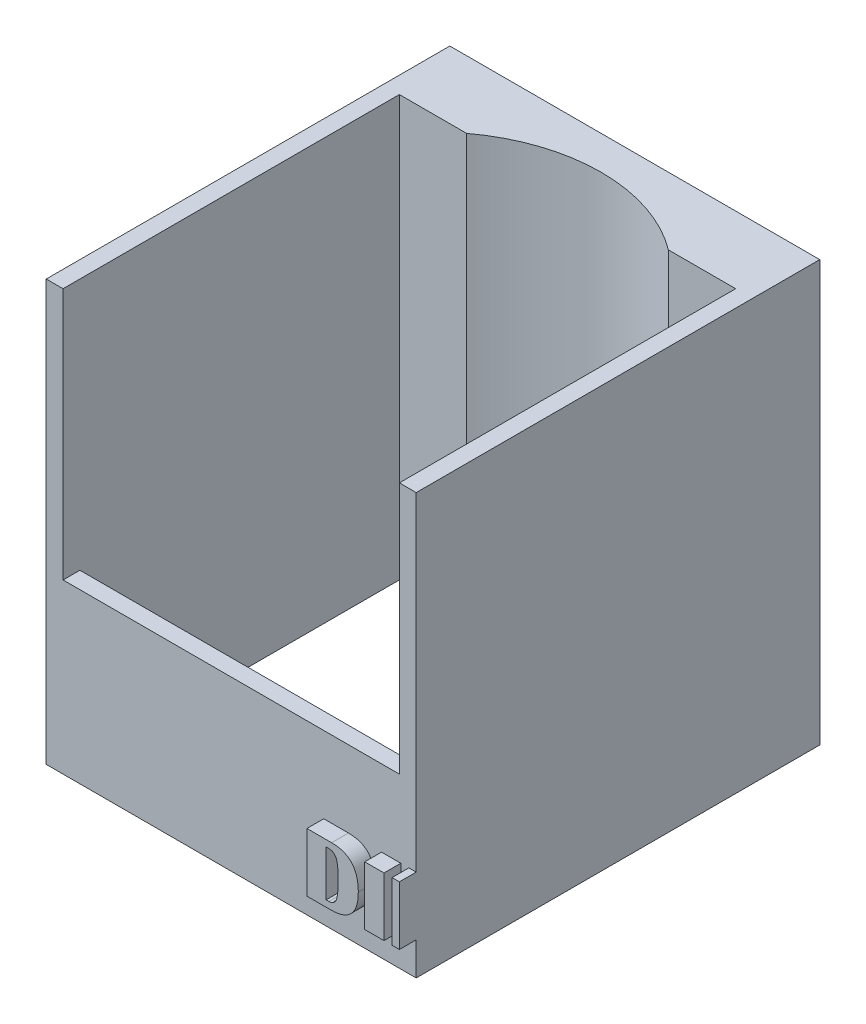
SolidWorks part; units mm, degrees
ref_plane "정면" through (0, 0, 0) normal (0, 0, 1) x (1, 0, 0)
ref_plane "윗면" through (0, 0, 0) normal (0, 1, 0) x (1, 0, 0)
ref_plane "우측면" through (0, 0, 0) normal (1, 0, 0) x (0, 0, -1)
sketch "Sketch1" plane through (0, 0, 0) normal (0, 1, 0) x (1, 0, 0)
  line L1 (0, 0) -> (670, 0)
  line L2 (0, 0) -> (0, 120)
  line L3 (0, 120) -> (670, 120)
  line L4 (670, 0) -> (670, 120)
  dimension "700" = 670
  dimension "D2" = 120
extrude "Boss-Extrude1" add sketch "Sketch1" along normal blind 530
sketch "Sketch2" plane through (0, 0, 0) normal (0, 0, 1) x (1, 0, 0)
  line L0 (0, 530) -> (0, 0) construction
  line L1 (10, 280) -> (110, 280)
  line L2 (10, 280) -> (10, 480)
  line L3 (10, 480) -> (110, 480)
  line L4 (110, 280) -> (110, 480)
  line L5 (0, 0) -> (670, 0) construction
  line L6 (120, 280) -> (120, 480)
  line L7 (120, 280) -> (220, 280)
  line L8 (220, 280) -> (220, 480)
  line L9 (120, 480) -> (220, 480)
  line L10 (230, 280) -> (230, 480)
  line L11 (230, 280) -> (330, 280)
  line L12 (330, 280) -> (330, 480)
  line L13 (230, 480) -> (330, 480)
  line L14 (340, 280) -> (340, 480)
  line L15 (340, 280) -> (440, 280)
  line L16 (440, 280) -> (440, 480)
  line L17 (340, 480) -> (440, 480)
  line L18 (450, 280) -> (450, 480)
  line L19 (450, 280) -> (550, 280)
  line L20 (550, 280) -> (550, 480)
  line L21 (450, 480) -> (550, 480)
  line L22 (560, 280) -> (560, 480)
  line L23 (560, 280) -> (660, 280)
  line L24 (660, 280) -> (660, 480)
  line L25 (560, 480) -> (660, 480)
  line L27 (10, 10) -> (660, 10)
  line L28 (10, 10) -> (10, 260)
  line L29 (10, 260) -> (660, 260)
  line L30 (660, 10) -> (660, 260)
  line L31 (0, 530) -> (670, 530) construction
  point P6 (10, 380)
  dimension "D1" = 100
  dimension "D2" = 200
  dimension "D3" = 10
  dimension "D4" = 50
  dimension "D6" = 10
  dimension "D7" = 20
  dimension "D5" = 6
extrude "Cut-Extrude1" cut sketch "Sketch2" against normal blind 100
sketch "Sketch3" plane through (0, 530, 0) normal (0, 1, 0) x (1, 0, 0)
  line L1 (670, 120) -> (0, 120) construction
  line L2 (0, 120) -> (0, 0) construction
  circle A0 centre (60, 60) radius 50
  circle A1 centre (170, 60) radius 50
  circle A2 centre (280, 60) radius 50
  circle A3 centre (390, 60) radius 50
  circle A4 centre (500, 60) radius 50
  circle A5 centre (610, 60) radius 50
  dimension "D1" = 100
  dimension "D2" = 10
  dimension "D3" = 10
  dimension "D4" = 6
extrude "Cut-Extrude2" cut sketch "Sketch3" against normal blind 260
hole_wizard "Ø12.0 (12) Diameter Hole2" positions "3DSketch1" profile "Sketch7" hole size "Ø12.0" standard "Ansi Metric"
sketch3d "3DSketch1"
  point P0 (59.7046, 270, -102.4117)
  point P2 (171.5567, 270, -102.6076)
  point P4 (280.8723, 270, -102.3969)
  point P6 (391.0687, 270, -102.7535)
  point P8 (500.7133, 270, -101.754)
  point P10 (609.5165, 270, -101.1227)
sketch "Sketch7" plane through (59.7046, 270, -102.4117) normal (1, 0, 0) x (0, 0, 1)
  line L0 (0, 0) -> (0, 33.6052)
  line L1 (0, 33.6052) -> (6, 30)
  line L2 (6, 30) -> (6, 0)
  line L5 (6, 0) -> (0, 0)
  line L10 (0, 33.6052) -> (-6, 30) construction
  line L11 (0, -6.35) -> (0, 107.95) construction
  dimension "구멍 지름" = 12
  dimension "구멍 깊이" = 30
  dimension "드릴 각도" = 118
sketch "Sketch8" plane through (0, 0, 0) normal (0, 0, 1) x (1, 0, 0)
  line L0 (660, 280) -> (660, 480) construction
  line L1 (10, 280) -> (660, 280)
  line L2 (10, 280) -> (10, 330)
  line L3 (10, 330) -> (660, 330)
  line L4 (660, 280) -> (660, 330)
  dimension "D1" = 50
extrude "Boss-Extrude2" add sketch "Sketch8" against normal blind 5
sketch "Sketch9" plane through (670, 0, 0) normal (1, 0, 0) x (0, 0, -1)
  line L0 (0, 530) -> (0, 0) construction
  line L1 (10, 10) -> (20, 10)
  line L2 (10, 10) -> (10, 260)
  line L3 (10, 260) -> (20, 260)
  line L4 (20, 10) -> (20, 260)
  line L5 (0, 0) -> (120, 0) construction
  dimension "D1" = 10
  dimension "D2" = 10
  dimension "D3" = 10
  dimension "D4" = 250
extrude "Cut-Extrude3" cut sketch "Sketch9" against normal blind 717
sketch "Sketch10" plane through (0, 10, 0) normal (0, 1, 0) x (1, 0, 0)
  line L0 (670, 120) -> (0, 120) construction
  line L1 (365, 61.9436) -> (350, 87.9243)
  line L2 (350, 87.9243) -> (320, 87.9243)
  line L3 (320, 87.9243) -> (305, 61.9436)
  line L4 (305, 61.9436) -> (320, 35.9628)
  line L5 (320, 35.9628) -> (350, 35.9628)
  line L6 (350, 35.9628) -> (365, 61.9436)
  line L7 (0, 120) -> (0, 0) construction
  circle A0 centre (335, 61.9436) radius 25.9808 construction
  dimension "D1" = 60
  dimension "D2" = 305
extrude "Cut-Extrude4" cut sketch "Sketch10" against normal blind 5
sketch "Sketch11" plane through (0, 0, -100) normal (0, 0, 1) x (1, 0, 0)
  line L0 (10, 10) -> (660, 10) construction
  line L1 (250, 10) -> (260, 10)
  line L2 (250, 10) -> (250, 110)
  line L3 (250, 110) -> (260, 110)
  line L4 (260, 10) -> (260, 110)
  line L5 (660, 10) -> (660, 260) construction
  line L6 (410, 10) -> (420, 10)
  line L7 (410, 10) -> (410, 110)
  line L8 (410, 110) -> (420, 110)
  line L9 (420, 10) -> (420, 110)
  line L10 (25, 198.4569) -> (325, 145.5588)
  line L11 (325, 145.5588) -> (325, 122.0178)
  line L12 (325, 122.0178) -> (345, 122.0178)
  line L13 (345, 122.0178) -> (345, 145.5588)
  line L14 (345, 145.5588) -> (645, 198.4569)
  line L15 (645, 198.4569) -> (25, 198.4569)
  point P18 (345, 133.7883)
  dimension "D1" = 10
  dimension "D2" = 10
  dimension "D3" = 100
  dimension "D4" = 100
  dimension "D5" = 150
  dimension "D6" = 240
  dimension "D7" = 20
  dimension "D8" = 65
  dimension "D9" = 100
  dimension "D10" = 620
  dimension "D11" = 100
extrude "Boss-Extrude3" add sketch "Sketch11" along normal blind 78 separate body
sketch "Sketch12" plane through (0, 0, -100) normal (0, 0, 1) x (1, 0, 0)
  line L0 (660, 260) -> (10, 260) construction
  line L1 (75.1986, 260) -> (95.1986, 260)
  line L2 (75.1986, 260) -> (75.1986, 230)
  line L3 (75.1986, 230) -> (95.1986, 230)
  line L4 (95.1986, 260) -> (95.1986, 230)
  line L5 (65.1986, 260) -> (65.1986, 240) construction
  line L6 (185.1986, 260) -> (185.1986, 230)
  line L7 (185.1986, 260) -> (205.1986, 260)
  line L8 (205.1986, 260) -> (205.1986, 230)
  line L9 (185.1986, 230) -> (205.1986, 230)
  line L10 (295.1986, 260) -> (295.1986, 230)
  line L11 (295.1986, 260) -> (315.1986, 260)
  line L12 (315.1986, 260) -> (315.1986, 230)
  line L13 (295.1986, 230) -> (315.1986, 230)
  line L14 (405.1986, 260) -> (405.1986, 230)
  line L15 (405.1986, 260) -> (425.1986, 260)
  line L16 (425.1986, 260) -> (425.1986, 230)
  line L17 (405.1986, 230) -> (425.1986, 230)
  line L18 (515.1986, 260) -> (515.1986, 230)
  line L19 (515.1986, 260) -> (535.1986, 260)
  line L20 (535.1986, 260) -> (535.1986, 230)
  line L21 (515.1986, 230) -> (535.1986, 230)
  line L22 (625.1986, 260) -> (625.1986, 230)
  line L23 (625.1986, 260) -> (645.1986, 260)
  line L24 (645.1986, 260) -> (645.1986, 230)
  line L25 (625.1986, 230) -> (645.1986, 230)
  dimension "D1" = 20
  dimension "D2" = 30
  dimension "D3" = 10
  dimension "D4" = 6
extrude "Cut-Extrude5" cut sketch "Sketch12" against normal blind 80
sketch "Sketch15" plane through (345, 0, 0) normal (1, 0, 0) x (0, 0, -1)
  line L0 (20, 10) -> (20, 260) construction
  line L1 (20, 121.4638) -> (50, 121.4638)
  line L2 (20, 121.4638) -> (20, 145)
  line L3 (20, 145) -> (50, 145)
  line L4 (50, 121.4638) -> (50, 145)
  line L5 (120, 530) -> (120, 0) construction
  line L6 (100, 116.0134) -> (70, 116.0134)
  line L7 (100, 116.0134) -> (100, 145)
  line L8 (100, 145) -> (70, 145)
  line L9 (70, 116.0134) -> (70, 145)
  line L10 (20, 260) -> (10, 260) construction
  dimension "D1" = 20
  dimension "D2" = 20
  dimension "D3" = 115
  dimension "D4" = 30
extrude "Cut-Extrude7" cut sketch "Sketch15" against normal blind 35
shell "Shell1" thickness 3
sketch "Sketch16" plane through (0, 122.0178, 0) normal (0, -1, 0) x (1, 0, 0)
  line L0 (345, -50) -> (325, -50) construction
  line L1 (328, -53) -> (342, -53)
  line L2 (328, -53) -> (328, -67)
  line L3 (328, -67) -> (342, -67)
  line L4 (342, -53) -> (342, -67)
  line L5 (325, -50) -> (325, -70) construction
  line L6 (345, -50) -> (345, -70) construction
  line L7 (325, -70) -> (345, -70) construction
  dimension "D1" = 3
  dimension "D2" = 3
  dimension "D3" = 3
  dimension "D4" = 3
extrude "Cut-Extrude8" cut sketch "Sketch16" against normal blind 35
sketch "Sketch17" plane through (0, 0, 0) normal (0, 0, 1) x (1, 0, 0)
  text T0 "<b>DIFF_USER</b>" font "Britannic Bold" height in points 72
extrude "Boss-Extrude4" add sketch "Sketch17" along normal blind 5
sketch "Sketch18" plane through (0, 0, 0) normal (0, 0, 1) x (1, 0, 0)
  line L0 (670, 530) -> (670, 0) construction
  line L1 (0, 0) -> (670, 0)
  line L2 (0, 0) -> (0, 280)
  line L3 (0, 280) -> (670, 280)
  line L4 (670, 0) -> (670, 280)
  dimension "D1" = 280
extrude "Cut-Extrude10" cut sketch "Sketch18" against normal blind 159
sketch "Sketch19" plane through (0, 0, 0) normal (0, 0, 1) x (1, 0, 0)
  line L0 (0, 530) -> (670, 530) construction
  line L1 (670, 280) -> (555, 280)
  line L2 (670, 280) -> (670, 530)
  line L3 (670, 530) -> (555, 530)
  line L4 (555, 280) -> (555, 530)
  line L5 (670, 280) -> (0, 280) construction
  line L6 (0, 530) -> (445, 530)
  line L7 (0, 530) -> (0, 280)
  line L8 (0, 280) -> (445, 280)
  line L9 (445, 530) -> (445, 280)
  dimension "D1" = 115
  dimension "D2" = 110
extrude "Cut-Extrude11" cut sketch "Sketch19" against normal through all both and the other way through all
sketch "Sketch20" plane through (0, 0, 0) normal (0, 0, 1) x (1, 0, 0)
  line L0 (555, 307.2638) -> (555, 530) construction
  line L1 (445, 530) -> (555, 530)
  line L2 (445, 530) -> (445, 405)
  line L3 (445, 405) -> (555, 405)
  line L4 (555, 530) -> (555, 405)
  dimension "D1" = 125
extrude "Cut-Extrude12" cut sketch "Sketch20" against normal through all both and the other way through all
